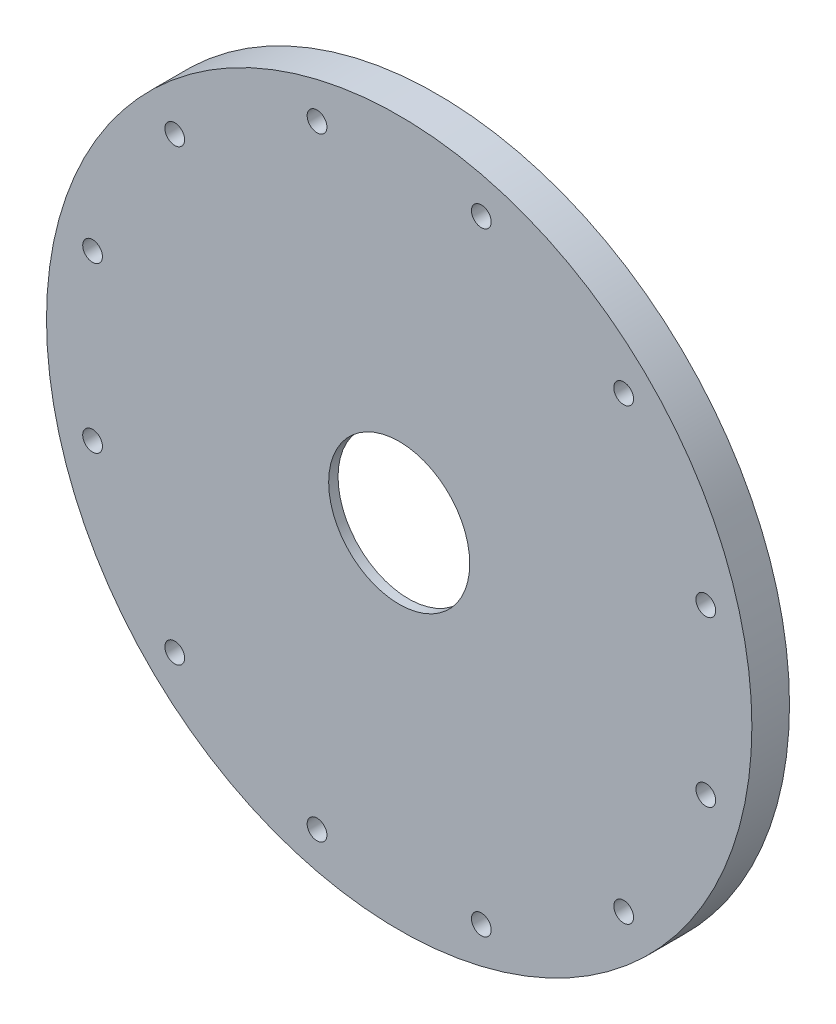
SolidWorks part; units mm, degrees
ref_plane "Front" through (0, 0, 0) normal (0, 0, 1) x (1, 0, 0)
ref_plane "Top" through (0, 0, 0) normal (0, 1, 0) x (1, 0, 0)
ref_plane "Right" through (0, 0, 0) normal (1, 0, 0) x (0, 0, -1)
sketch "Sketch1" plane through (0, 0, 0) normal (0, 0, 1) x (1, 0, 0)
  circle A0 centre (0, 0) radius 75
  dimension "D1" = 150
extrude "Boss-Extrude1" add sketch "Sketch1" along normal blind 8
hole_wizard "M5x0.8 Tapped Hole1" positions "Sketch3" profile "Sketch5" tap size "M5x0.8" standard "ANSI Metric" end condition up to next
sketch "Sketch3" plane through (0, 0, 0) normal (0, 0, -1) x (-1, 0, 0)
  line L14 (0, 0) -> (0, -75) construction
  line L15 (17.4703, -65.2) -> (-17.4703, 65.2) construction
  line L17 (65.2, 17.4703) -> (-65.2, -17.4703) construction
  line L19 (47.7297, 47.7297) -> (-47.7297, -47.7297) construction
  line L21 (0, 0) -> (17.4703, -65.2) construction
  line L23 (-17.4703, -65.2) -> (17.4703, 65.2) construction
  line L24 (-65.2, 17.4703) -> (65.2, -17.4703) construction
  line L26 (-47.7297, 47.7297) -> (47.7297, -47.7297) construction
  circle A1 centre (0, 0) radius 75 construction
  circle A3 centre (0, 0) radius 67.5 construction
  point P5 (-47.7297, 47.7297)
  point P11 (65.2, -17.4703)
  point P13 (47.7297, -47.7297)
  point P21 (-65.2, 17.4703)
  point P62 (-17.4703, 65.2)
  point P64 (-65.2, -17.4703)
  point P66 (-47.7297, -47.7297)
  point P68 (17.4703, -65.2)
  point P70 (17.4703, -65.2)
  point P72 (65.2, 17.4703)
  point P74 (47.7297, 47.7297)
  point P450 (17.4703, 65.2)
  point P453 (-17.4703, -65.2)
  dimension "D1" = 30
  dimension "D2" = 135
  dimension "D3" = 30
  dimension "D4" = 15
  dimension "D5" = 30
  dimension "D6" = 30
  dimension "D7" = 30
sketch "Sketch5" plane through (17.4703, -65.2, 0) normal (1, 0, 0) x (0, 1, 0)
  line L0 (0, 0) -> (0, 8)
  line L1 (0, 8) -> (2.1, 8)
  line L2 (2.1, 8) -> (2.1, 0)
  line L5 (2.1, 0) -> (0, 0)
  line L11 (0, -6.35) -> (0, 107.95) construction
  dimension "Thru Tap Drill Dia." = 4.2
  dimension "Thru Tap Drill Depth" = 8
cosmetic thread "Hole Thread1" parameters "D2"=5
cosmetic thread "Hole Thread2" parameters "D2"=5
cosmetic thread "Hole Thread3" parameters "D2"=5
cosmetic thread "Hole Thread4" parameters "D2"=5
cosmetic thread "Hole Thread5" parameters "D2"=5
cosmetic thread "Hole Thread6" parameters "D2"=5
cosmetic thread "Hole Thread7" parameters "D2"=5
cosmetic thread "Hole Thread8" parameters "D2"=5
cosmetic thread "Hole Thread9" parameters "D2"=5
cosmetic thread "Hole Thread10" parameters "D2"=5
cosmetic thread "Hole Thread11" parameters "D2"=5
cosmetic thread "Hole Thread12" parameters "D2"=5
sketch "Sketch6" plane through (0, 0, 8) normal (0, 0, -1) x (-1, 0, 0)
  line L0 (0, 0) -> (-47.7297, 47.7297) construction
  line L25 (-43.2683, 46.5343) -> (-44.4637, 50.9957)
  line L26 (-44.4637, 50.9957) -> (-48.9251, 52.1911)
  line L27 (-48.9251, 52.1911) -> (-52.1911, 48.9251)
  line L28 (-52.1911, 48.9251) -> (-50.9957, 44.4637)
  line L29 (-50.9957, 44.4637) -> (-46.5343, 43.2683)
  line L30 (-46.5343, 43.2683) -> (-43.2683, 46.5343)
  line L79 (-13.0089, 66.3954) -> (-16.2749, 69.6614)
  line L80 (-14.2043, 61.934) -> (-13.0089, 66.3954)
  line L81 (-18.6657, 60.7386) -> (-14.2043, 61.934)
  line L82 (-21.9317, 64.0046) -> (-18.6657, 60.7386)
  line L83 (-20.7363, 68.466) -> (-21.9317, 64.0046)
  line L84 (-16.2749, 69.6614) -> (-20.7363, 68.466)
  line L85 (21.9317, 64.0046) -> (20.7363, 68.466)
  line L86 (18.6657, 60.7386) -> (21.9317, 64.0046)
  line L87 (14.2043, 61.934) -> (18.6657, 60.7386)
  line L88 (13.0089, 66.3954) -> (14.2043, 61.934)
  line L89 (16.2749, 69.6614) -> (13.0089, 66.3954)
  line L90 (20.7363, 68.466) -> (16.2749, 69.6614)
  line L91 (50.9957, 44.4637) -> (52.1911, 48.9251)
  line L92 (46.5343, 43.2683) -> (50.9957, 44.4637)
  line L93 (43.2683, 46.5343) -> (46.5343, 43.2683)
  line L94 (44.4637, 50.9957) -> (43.2683, 46.5343)
  line L95 (48.9251, 52.1911) -> (44.4637, 50.9957)
  line L96 (52.1911, 48.9251) -> (48.9251, 52.1911)
  line L97 (66.3954, 13.0089) -> (69.6614, 16.2749)
  line L98 (61.934, 14.2043) -> (66.3954, 13.0089)
  line L99 (60.7386, 18.6657) -> (61.934, 14.2043)
  line L100 (64.0046, 21.9317) -> (60.7386, 18.6657)
  line L101 (68.466, 20.7363) -> (64.0046, 21.9317)
  line L102 (69.6614, 16.2749) -> (68.466, 20.7363)
  line L103 (64.0046, -21.9317) -> (68.466, -20.7363)
  line L104 (60.7386, -18.6657) -> (64.0046, -21.9317)
  line L105 (61.934, -14.2043) -> (60.7386, -18.6657)
  line L106 (66.3954, -13.0089) -> (61.934, -14.2043)
  line L107 (69.6614, -16.2749) -> (66.3954, -13.0089)
  line L108 (68.466, -20.7363) -> (69.6614, -16.2749)
  line L109 (44.4637, -50.9957) -> (48.9251, -52.1911)
  line L110 (43.2683, -46.5343) -> (44.4637, -50.9957)
  line L111 (46.5343, -43.2683) -> (43.2683, -46.5343)
  line L112 (50.9957, -44.4637) -> (46.5343, -43.2683)
  line L113 (52.1911, -48.9251) -> (50.9957, -44.4637)
  line L114 (48.9251, -52.1911) -> (52.1911, -48.9251)
  line L115 (13.0089, -66.3954) -> (16.2749, -69.6614)
  line L116 (14.2043, -61.934) -> (13.0089, -66.3954)
  line L117 (18.6657, -60.7386) -> (14.2043, -61.934)
  line L118 (21.9317, -64.0046) -> (18.6657, -60.7386)
  line L119 (20.7363, -68.466) -> (21.9317, -64.0046)
  line L120 (16.2749, -69.6614) -> (20.7363, -68.466)
  line L121 (-21.9317, -64.0046) -> (-20.7363, -68.466)
  line L122 (-18.6657, -60.7386) -> (-21.9317, -64.0046)
  line L123 (-14.2043, -61.934) -> (-18.6657, -60.7386)
  line L124 (-13.0089, -66.3954) -> (-14.2043, -61.934)
  line L125 (-16.2749, -69.6614) -> (-13.0089, -66.3954)
  line L126 (-20.7363, -68.466) -> (-16.2749, -69.6614)
  line L127 (-50.9957, -44.4637) -> (-52.1911, -48.9251)
  line L128 (-46.5343, -43.2683) -> (-50.9957, -44.4637)
  line L129 (-43.2683, -46.5343) -> (-46.5343, -43.2683)
  line L130 (-44.4637, -50.9957) -> (-43.2683, -46.5343)
  line L131 (-48.9251, -52.1911) -> (-44.4637, -50.9957)
  line L132 (-52.1911, -48.9251) -> (-48.9251, -52.1911)
  line L133 (-66.3954, -13.0089) -> (-69.6614, -16.2749)
  line L134 (-61.934, -14.2043) -> (-66.3954, -13.0089)
  line L135 (-60.7386, -18.6657) -> (-61.934, -14.2043)
  line L136 (-64.0046, -21.9317) -> (-60.7386, -18.6657)
  line L137 (-68.466, -20.7363) -> (-64.0046, -21.9317)
  line L138 (-69.6614, -16.2749) -> (-68.466, -20.7363)
  line L139 (-64.0046, 21.9317) -> (-68.466, 20.7363)
  line L140 (-60.7386, 18.6657) -> (-64.0046, 21.9317)
  line L141 (-61.934, 14.2043) -> (-60.7386, 18.6657)
  line L142 (-66.3954, 13.0089) -> (-61.934, 14.2043)
  line L143 (-69.6614, 16.2749) -> (-66.3954, 13.0089)
  line L144 (-68.466, 20.7363) -> (-69.6614, 16.2749)
  circle A6 centre (-47.7297, 47.7297) radius 4 construction
  circle A13 centre (-47.7297, 47.7297) radius 2.1 construction
  point P80 (0, 0)
  point P111 (-44.9013, 44.9013)
  dimension "D1" = 12
  dimension "D8" = 8
extrude "Cut-Extrude2" [suppressed] cut sketch "Sketch6" along normal blind 4.2
hole_wizard "Ø5.0mm Dowel Hole1" [suppressed] positions "Sketch8" profile "Sketch10" hole size "Ø5.0" standard "ANSI Metric"
sketch "Sketch8" plane through (0, 0, 0) normal (0, 0, -1) x (-1, 0, 0)
  circle A1 centre (0, 0) radius 67.5 construction
  point P545 (-30.1011, -60.4167)
  point P547 (-30.1011, 60.4167)
sketch "Sketch10" plane through (30.1011, 60.4167, 0) normal (1, 0, 0) x (0, 1, 0)
  line L0 (0, 0) -> (0, 6.4421)
  line L1 (0, 6.4421) -> (2.4, 5)
  line L2 (2.4, 5) -> (2.4, 0)
  line L5 (2.4, 0) -> (0, 0)
  line L10 (0, 6.4421) -> (-2.4, 5) construction
  line L11 (0, -6.35) -> (0, 107.95) construction
  dimension "Hole Dia." = 4.8
  dimension "Hole Depth" = 5
  dimension "Drill Angle" = 118
sketch "Sketch11" plane through (0, 0, 0) normal (0, 0, -1) x (-1, 0, 0)
  circle A0 centre (0, 0) radius 50.2
  dimension "D1" = 100.4
extrude "Cut-Extrude3" cut sketch "Sketch11" against normal blind 6
sketch "Sketch12" plane through (0, 0, 0) normal (0, 0, -1) x (-1, 0, 0)
  circle A0 centre (0, 0) radius 53.6575
  circle A1 centre (0, 0) radius 58.6475
  dimension "D1" = 107.315
  dimension "D2" = 4.99
extrude "Cut-Extrude4" cut sketch "Sketch12" against normal blind 4
sketch "Sketch13" plane through (0, 0, 6) normal (0, 0, -1) x (-1, 0, 0)
  circle A0 centre (0, 0) radius 15
  dimension "D1" = 30
extrude "Cut-Extrude5" cut sketch "Sketch13" against normal up to surface (2 mm away) up to face at (49.8297, 47.7297, 8)
